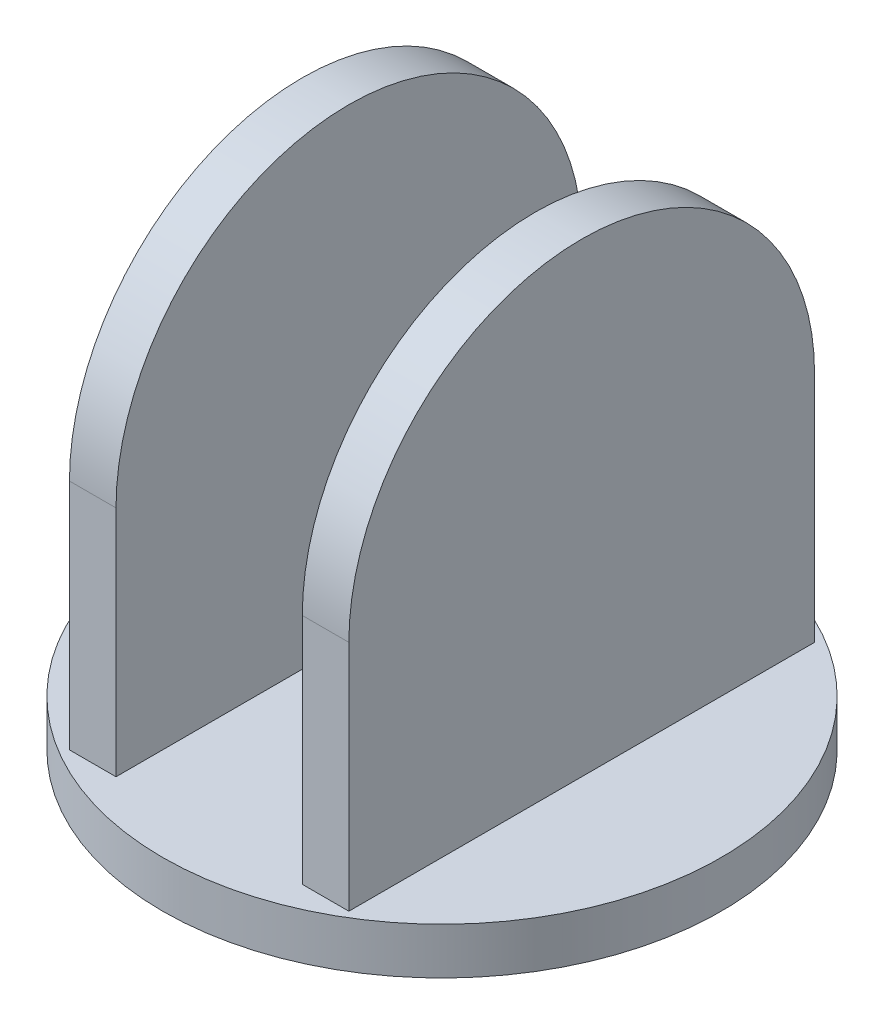
SolidWorks part; units mm, degrees
ref_plane "Front Plane" through (0, 0, 0) normal (0, 0, 1) x (1, 0, 0)
ref_plane "Top Plane" through (0, 0, 0) normal (0, 1, 0) x (1, 0, 0)
ref_plane "Right Plane" through (0, 0, 0) normal (1, 0, 0) x (0, 0, -1)
sketch "Sketch1" plane through (0, 0, 0) normal (0, 1, 0) x (1, 0, 0)
  circle A0 centre (0, 0) radius 60
  dimension "D1" = 120
extrude "Boss-Extrude1" add sketch "Sketch1" against normal blind 10
sketch "Sketch2" plane through (0, 0, 0) normal (1, 0, 0) x (0, 0, -1)
  line L0 (0, 0) -> (50, 0)
  line L1 (60, 0) -> (-60, 0) construction
  line L2 (50, 0) -> (50, 50)
  line L3 (-50, 50) -> (-50, 0)
  line L4 (-50, 0) -> (0, 0)
  arc A0 (50, 50) -> (-50, 50) centre (0, 50) ccw
  point P8 (0, 0)
  point P11 (0, 0)
  point P12 (0, 0)
  point P13 (0, 0)
  dimension "D1" = 50
  dimension "D3" = 50
  dimension "D2" = 50
extrude "Boss-Extrude2" add sketch "Sketch2" along normal blind 10 from offset 20
mirror "Mirror1" about plane through (0, 0, 0) normal (1, 0, 0) of "Boss-Extrude2"
